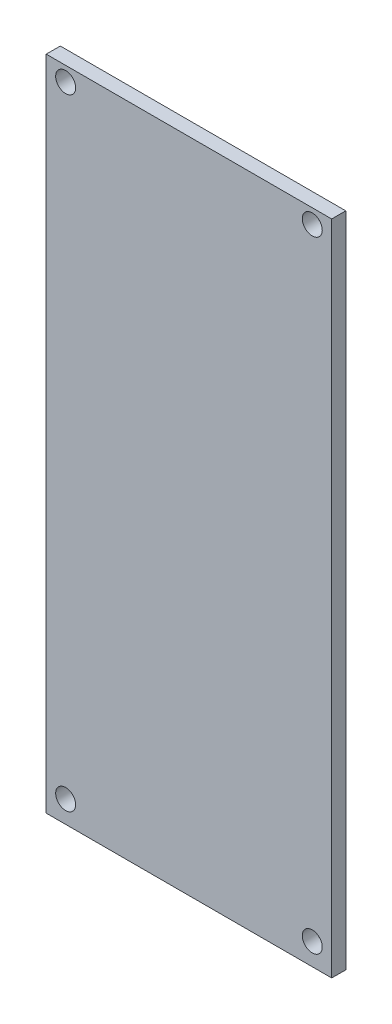
SolidWorks part; units mm, degrees
ref_plane "Front Plane" through (0, 0, 0) normal (0, 0, 1) x (1, 0, 0)
ref_plane "Top Plane" through (0, 0, 0) normal (0, 1, 0) x (1, 0, 0)
ref_plane "Right Plane" through (0, 0, 0) normal (1, 0, 0) x (0, 0, -1)
sketch "Sketch1" plane through (0, 0, 0) normal (0, 0, 1) x (1, 0, 0)
  line L0 (0, 34.5981) -> (0, -35.4019) construction
  line L1 (-15.2, -35.4019) -> (15.2, -35.4019)
  line L2 (-15.2, -35.4019) -> (-15.2, 34.5981)
  line L3 (-15.2, 34.5981) -> (15.2, 34.5981)
  line L4 (15.2, -35.4019) -> (15.2, 34.5981)
  line L5 (-13.13, -33.06) -> (13.13, -33.06) construction
  line L6 (-13.13, -33.06) -> (-13.13, 33.06) construction
  line L7 (-13.13, 33.06) -> (13.13, 33.06) construction
  line L8 (13.13, -33.06) -> (13.13, 33.06) construction
  line L9 (-13.13, -33.06) -> (13.13, 33.06) construction
  line L10 (-13.13, 33.06) -> (13.13, -33.06) construction
  line L11 (0, 0) -> (-13.13, 0) construction
  circle A0 centre (13.13, 33.06) radius 1.065
  circle A1 centre (-13.13, 33.06) radius 1.065
  circle A2 centre (-13.13, -33.06) radius 1.065
  circle A3 centre (13.13, -33.06) radius 1.065
  point P0 (0, 0)
  point P6 (0, 0)
  dimension "D5" = 2.13
  dimension "D1" = 70
  dimension "D2" = 30.4
  dimension "D3" = 26.26
  dimension "D4" = 66.12
extrude "Boss-Extrude1" add sketch "Sketch1" along normal blind 1.5
